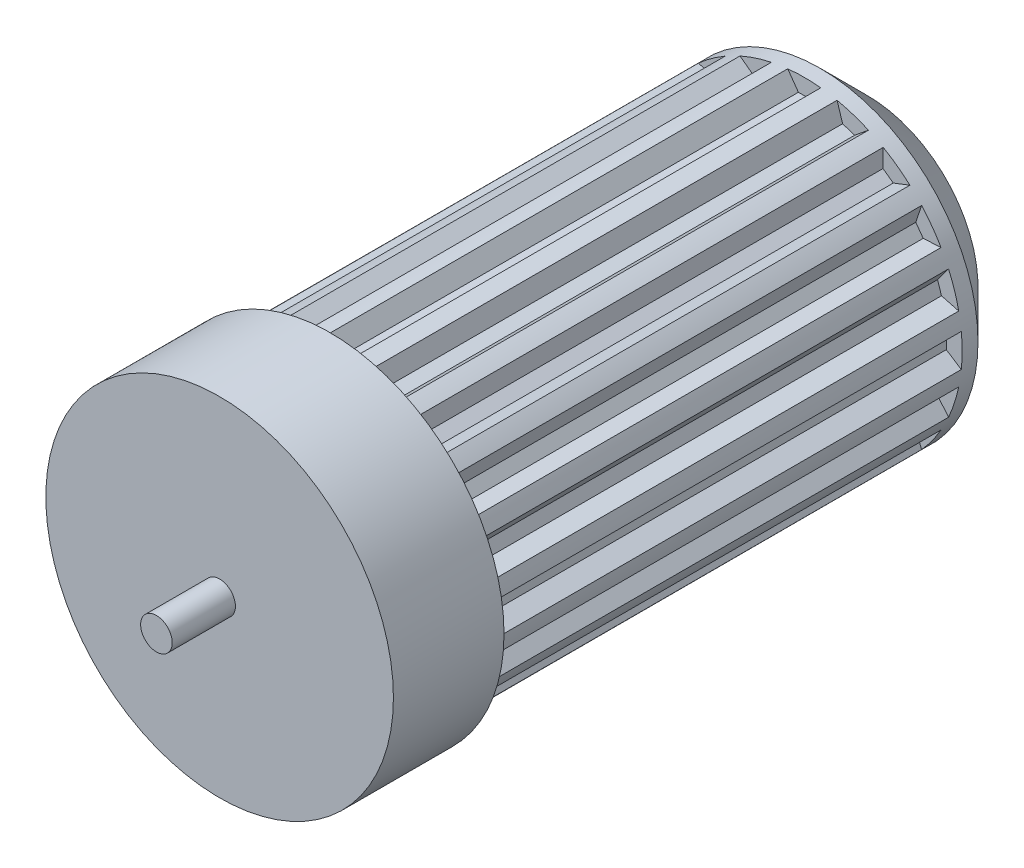
SolidWorks part; units mm, degrees
ref_plane "Front Plane" through (0, 0, 0) normal (0, 0, 1) x (1, 0, 0)
ref_plane "Top Plane" through (0, 0, 0) normal (0, 1, 0) x (1, 0, 0)
ref_plane "Right Plane" through (0, 0, 0) normal (1, 0, 0) x (0, 0, -1)
sketch "Sketch1" plane through (0, 0, 0) normal (0, 0, 1) x (1, 0, 0)
  circle A0 centre (0, 0) radius 100
  dimension "D1" = 200
extrude "Boss-Extrude1" add sketch "Sketch1" along normal blind 300
sketch "Sketch2" plane through (0, 0, 300) normal (0, 0, 1) x (1, 0, 0)
  circle A0 centre (0, 0) radius 10
  dimension "D1" = 20
sketch "Sketch3" plane through (0, 0, 0) normal (0, 0, -1) x (-1, 0, 0)
  line L0 (-10.4669, 99.4507) -> (-4.3469, 89.9414)
  line L1 (-4.3469, 89.9414) -> (3.666, 89.9414)
  line L2 (3.666, 89.9414) -> (10.434, 99.4542)
  line L3 (0, 0) -> (0, 100) construction
  line L4 (20.7773, 97.8177) -> (23.6592, 86.8827)
  line L5 (23.6592, 86.8827) -> (31.28, 84.4065)
  line L6 (31.28, 84.4065) -> (40.6564, 91.3622)
  line L7 (49.9878, 86.6096) -> (49.3495, 75.3192)
  line L8 (49.3495, 75.3192) -> (55.8321, 70.6093)
  line L9 (55.8321, 70.6093) -> (66.899, 74.3271)
  line L10 (74.305, 66.9236) -> (70.2091, 56.383)
  line L11 (70.2091, 56.383) -> (74.919, 49.9004)
  line L12 (74.919, 49.9004) -> (86.5931, 50.0164)
  line L13 (91.3488, 40.6866) -> (84.1961, 31.9276)
  line L14 (84.1961, 31.9276) -> (86.6723, 24.3068)
  line L15 (86.6723, 24.3068) -> (97.8108, 20.8097)
  line L16 (99.4507, 10.4669) -> (89.9414, 4.3469)
  line L17 (89.9414, 4.3469) -> (89.9414, -3.666)
  line L18 (89.9414, -3.666) -> (99.4542, -10.434)
  line L19 (97.8177, -20.7773) -> (86.8827, -23.6592)
  line L20 (86.8827, -23.6592) -> (84.4065, -31.28)
  line L21 (84.4065, -31.28) -> (91.3622, -40.6564)
  line L22 (86.6096, -49.9878) -> (75.3192, -49.3495)
  line L23 (75.3192, -49.3495) -> (70.6093, -55.8321)
  line L24 (70.6093, -55.8321) -> (74.3271, -66.899)
  line L25 (66.9236, -74.305) -> (56.383, -70.2091)
  line L26 (56.383, -70.2091) -> (49.9004, -74.919)
  line L27 (49.9004, -74.919) -> (50.0164, -86.5931)
  line L28 (40.6866, -91.3488) -> (31.9276, -84.1961)
  line L29 (31.9276, -84.1961) -> (24.3068, -86.6723)
  line L30 (24.3068, -86.6723) -> (20.8097, -97.8108)
  line L31 (10.4669, -99.4507) -> (4.3469, -89.9414)
  line L32 (4.3469, -89.9414) -> (-3.666, -89.9414)
  line L33 (-3.666, -89.9414) -> (-10.434, -99.4542)
  line L34 (-20.7773, -97.8177) -> (-23.6592, -86.8827)
  line L35 (-23.6592, -86.8827) -> (-31.28, -84.4065)
  line L36 (-31.28, -84.4065) -> (-40.6564, -91.3622)
  line L37 (-49.9878, -86.6096) -> (-49.3495, -75.3192)
  line L38 (-49.3495, -75.3192) -> (-55.8321, -70.6093)
  line L39 (-55.8321, -70.6093) -> (-66.899, -74.3271)
  line L40 (-74.305, -66.9236) -> (-70.2091, -56.383)
  line L41 (-70.2091, -56.383) -> (-74.919, -49.9004)
  line L42 (-74.919, -49.9004) -> (-86.5931, -50.0164)
  line L43 (-91.3488, -40.6866) -> (-84.1961, -31.9276)
  line L44 (-84.1961, -31.9276) -> (-86.6723, -24.3068)
  line L45 (-86.6723, -24.3068) -> (-97.8108, -20.8097)
  line L46 (-99.4507, -10.4669) -> (-89.9414, -4.3469)
  line L47 (-89.9414, -4.3469) -> (-89.9414, 3.666)
  line L48 (-89.9414, 3.666) -> (-99.4542, 10.434)
  line L49 (-97.8177, 20.7773) -> (-86.8827, 23.6592)
  line L50 (-86.8827, 23.6592) -> (-84.4065, 31.28)
  line L51 (-84.4065, 31.28) -> (-91.3622, 40.6564)
  line L52 (-86.6096, 49.9878) -> (-75.3192, 49.3495)
  line L53 (-75.3192, 49.3495) -> (-70.6093, 55.8321)
  line L54 (-70.6093, 55.8321) -> (-74.3271, 66.899)
  line L55 (-66.9236, 74.305) -> (-56.383, 70.2091)
  line L56 (-56.383, 70.2091) -> (-49.9004, 74.919)
  line L57 (-49.9004, 74.919) -> (-50.0164, 86.5931)
  line L58 (-40.6866, 91.3488) -> (-31.9276, 84.1961)
  line L59 (-31.9276, 84.1961) -> (-24.3068, 86.6723)
  line L60 (-24.3068, 86.6723) -> (-20.8097, 97.8108)
  circle A0 centre (0, 0) radius 100 construction
  arc A1 (-20.8097, 97.8108) -> (-40.6866, 91.3488) centre (0, 0) ccw
  arc A2 (-50.0164, 86.5931) -> (-66.9236, 74.305) centre (0, 0) ccw
  arc A3 (-74.3271, 66.899) -> (-86.6096, 49.9878) centre (0, 0) ccw
  arc A4 (-91.3622, 40.6564) -> (-97.8177, 20.7773) centre (0, 0) ccw
  arc A5 (-97.8108, -20.8097) -> (-91.3488, -40.6866) centre (0, 0) ccw
  arc A6 (-99.4542, 10.434) -> (-99.4507, -10.4669) centre (0, 0) ccw
  arc A7 (-86.5931, -50.0164) -> (-74.305, -66.9236) centre (0, 0) ccw
  arc A8 (-66.899, -74.3271) -> (-49.9878, -86.6096) centre (0, 0) ccw
  arc A9 (-40.6564, -91.3622) -> (-20.7773, -97.8177) centre (0, 0) ccw
  arc A10 (-10.434, -99.4542) -> (10.4669, -99.4507) centre (0, 0) ccw
  arc A11 (20.8097, -97.8108) -> (40.6866, -91.3488) centre (0, 0) ccw
  arc A12 (50.0164, -86.5931) -> (66.9236, -74.305) centre (0, 0) ccw
  arc A13 (74.3271, -66.899) -> (86.6096, -49.9878) centre (0, 0) ccw
  arc A14 (91.3622, -40.6564) -> (97.8177, -20.7773) centre (0, 0) ccw
  arc A15 (99.4542, -10.434) -> (99.4507, 10.4669) centre (0, 0) ccw
  arc A16 (97.8108, 20.8097) -> (91.3488, 40.6866) centre (0, 0) ccw
  arc A17 (86.5931, 50.0164) -> (74.305, 66.9236) centre (0, 0) ccw
  arc A18 (66.899, 74.3271) -> (49.9878, 86.6096) centre (0, 0) ccw
  arc A19 (40.6564, 91.3622) -> (20.7773, 97.8177) centre (0, 0) ccw
  arc A20 (10.434, 99.4542) -> (-10.4669, 99.4507) centre (0, 0) ccw
  point P88 (0, 0)
  dimension "D1" = 20
extrude "Cut-Extrude1" cut sketch "Sketch3" against normal up to next
sketch "Sketch4" plane through (0, 0, 0) normal (0, 0, -1) x (-1, 0, 0)
  circle A0 centre (0, 0) radius 100
extrude "Boss-Extrude3" add sketch "Sketch4" along normal blind 40
chamfer "Chamfer1" distance 30 angle 45 1 edges at (-100, 0, -40)
sketch "Sketch5" plane through (0, 0, 300) normal (0, 0, 1) x (1, 0, 0)
  circle A0 centre (0, 0) radius 110
  dimension "D1" = 220
extrude "Boss-Extrude4" add sketch "Sketch5" along normal blind 70
sketch "Sketch6" plane through (0, 0, 370) normal (0, 0, 1) x (1, 0, 0)
  circle A0 centre (0, 0) radius 10
  dimension "D1" = 20
extrude "Boss-Extrude5" add sketch "Sketch6" along normal blind 40
